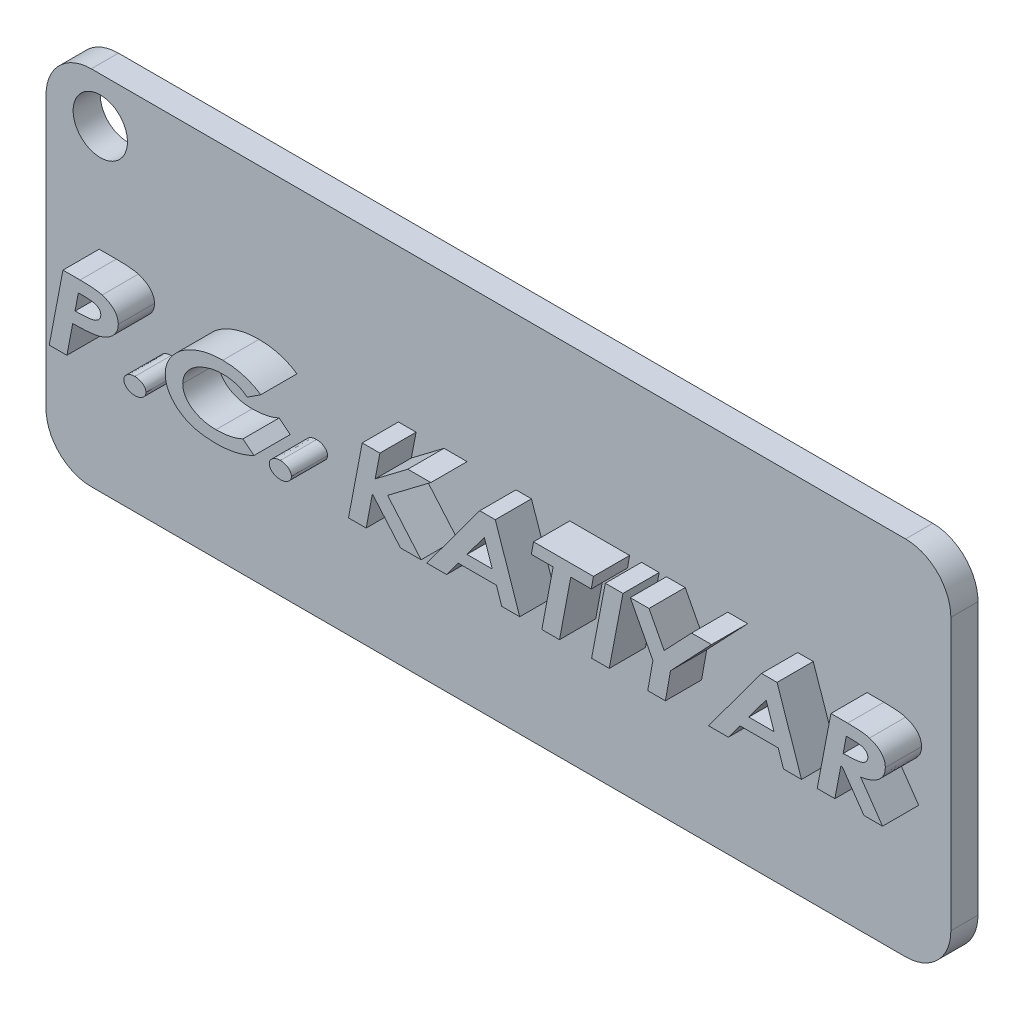
SolidWorks part; units mm, degrees
ref_plane "Front Plane" through (0, 0, 0) normal (0, 0, 1) x (1, 0, 0)
ref_plane "Top Plane" through (0, 0, 0) normal (0, 1, 0) x (1, 0, 0)
ref_plane "Right Plane" through (0, 0, 0) normal (1, 0, 0) x (0, 0, -1)
sketch "Sketch2" plane through (0, 0, 0) normal (0, 0, 1) x (1, 0, 0)
  line L1 (-22.5, -10) -> (22.5, -10)
  line L2 (-25, -7.5) -> (-25, 7.5)
  line L3 (-22.5, 10) -> (22.5, 10)
  line L4 (25, -7.5) -> (25, 7.5)
  line L5 (-25, -10) -> (25, 10) construction
  line L6 (-25, 10) -> (25, -10) construction
  arc A0 (-22.5, -10) -> (-25, -7.5) centre (-22.5, -7.5) cw
  arc A1 (25, -7.5) -> (22.5, -10) centre (22.5, -7.5) cw
  arc A2 (25, 7.5) -> (22.5, 10) centre (22.5, 7.5) ccw
  arc A3 (-22.5, 10) -> (-25, 7.5) centre (-22.5, 7.5) ccw
  point P0 (0, 0)
  dimension "D3" = 2.5
  dimension "D1" = 50
  dimension "D2" = 20
extrude "Boss-Extrude1" add sketch "Sketch2" against normal blind 7
sketch "Sketch3" plane through (0, 0, -7) normal (0, 0, -1) x (-1, 0, 0)
  line L0 (-25, -7.5) -> (-25, 7.5) construction
  line L1 (-20.5, -8) -> (20.5, -8)
  line L2 (-23, -5.5) -> (-23, 5.5)
  line L3 (-20.5, 8) -> (20.5, 8)
  line L4 (23, -5.5) -> (23, 5.5)
  line L5 (-23, -8) -> (23, 8) construction
  line L6 (-23, 8) -> (23, -8) construction
  line L7 (-22.5, 10) -> (22.5, 10) construction
  arc A0 (-20.5, -8) -> (-23, -5.5) centre (-20.5, -5.5) cw
  arc A1 (23, -5.5) -> (20.5, -8) centre (20.5, -5.5) cw
  arc A2 (23, 5.5) -> (20.5, 8) centre (20.5, 5.5) ccw
  arc A3 (-20.5, 8) -> (-23, 5.5) centre (-20.5, 5.5) ccw
  point P0 (0, 0)
  dimension "D1" = 2.5
  dimension "D2" = 2
  dimension "D3" = 2
extrude "Cut-Extrude2" cut sketch "Sketch3" against normal blind 2
sketch "Sketch5" plane through (0, 0, 0) normal (0, 0, 1) x (1, 0, 0)
  text T0 "P.C. KATIYAR" font "Century Gothic" height in points 15
extrude "Boss-Extrude2" add sketch "Sketch5" along normal blind 2
sketch "Sketch14" plane through (0, 0, -5) normal (0, 0, -1) x (-1, 0, 0)
  line L1 (-25, -10) -> (25, -10)
  line L2 (-25, -10) -> (-25, 10)
  line L3 (-25, 10) -> (25, 10)
  line L4 (25, -10) -> (25, 10)
  line L5 (-25, -10) -> (25, 10) construction
  line L6 (-25, 10) -> (25, -10) construction
  point P0 (0, 0)
  dimension "D1" = 20
  dimension "D2" = 50
extrude "Cut-Extrude8" cut sketch "Sketch14" along normal blind 2
sketch "Sketch15" plane through (0, 0, -5) normal (0, 0, -1) x (-1, 0, 0)
  line L1 (-25, -10) -> (25, -10)
  line L2 (-25, -10) -> (-25, 10)
  line L3 (-25, 10) -> (25, 10)
  line L4 (25, -10) -> (25, 10)
  line L5 (-25, -10) -> (25, 10) construction
  line L6 (-25, 10) -> (25, -10) construction
  point P0 (0, 0)
  dimension "D1" = 20
  dimension "D2" = 50
extrude "Cut-Extrude9" cut sketch "Sketch15" against normal blind 3.5
sketch "Sketch16" plane through (0, 0, 0) normal (0, 0, 1) x (1, 0, 0)
  line L0 (-25, 7.5) -> (-25, -7.5) construction
  line L1 (22.5, 10) -> (-22.5, 10) construction
  circle A0 centre (-22, 7.5) radius 1.5
  dimension "D1" = 3
  dimension "D2" = 2.5
extrude "Cut-Extrude10" cut sketch "Sketch16" against normal blind 3.5
